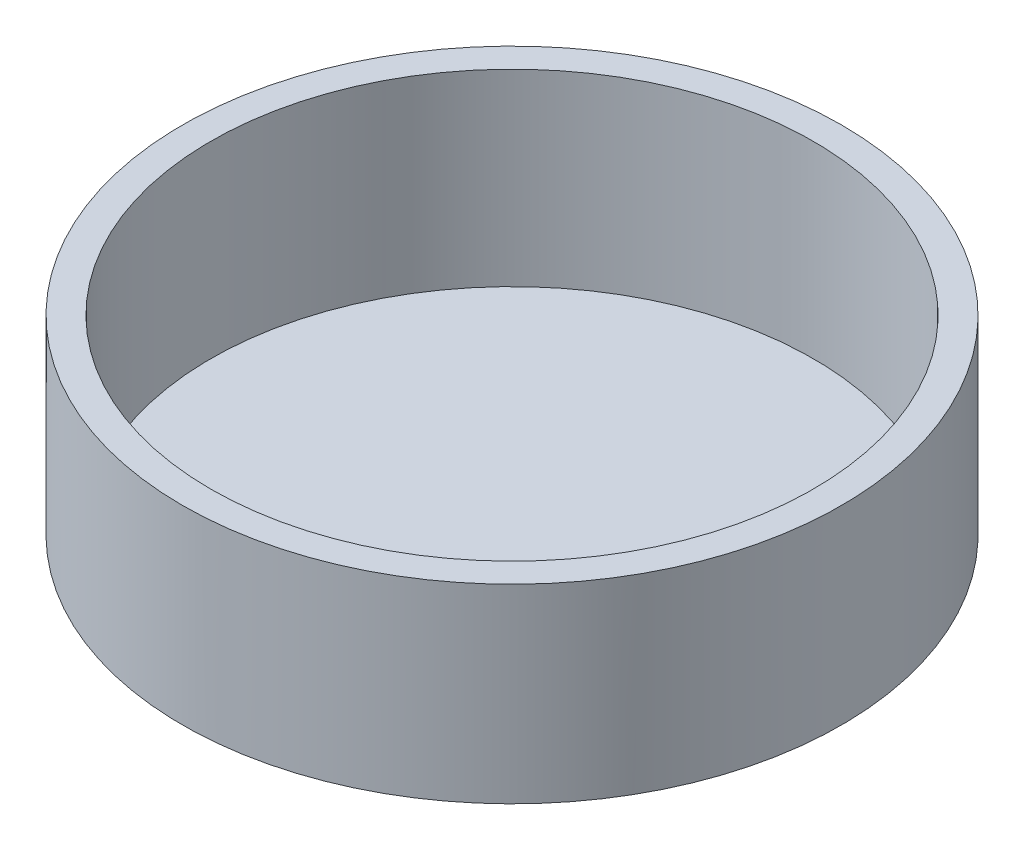
SolidWorks part; units mm, degrees
ref_plane "Front Plane" through (0, 0, 0) normal (0, 0, 1) x (1, 0, 0)
ref_plane "Top Plane" through (0, 0, 0) normal (0, 1, 0) x (1, 0, 0)
ref_plane "Right Plane" through (0, 0, 0) normal (1, 0, 0) x (0, 0, -1)
sketch "Sketch1" plane through (0, 0, 0) normal (0, 1, 0) x (1, 0, 0)
  circle A0 centre (0, 0) radius 17.5
  circle A1 centre (0, 0) radius 16
extrude "Boss-Extrude1" add sketch "Sketch1" along normal blind 10
sketch "Sketch2" plane through (0, 0, 0) normal (0, -1, 0) x (1, 0, 0)
  circle A0 centre (0, 0) radius 17.5
extrude "Boss-Extrude2" add sketch "Sketch2" along normal blind 0.1
